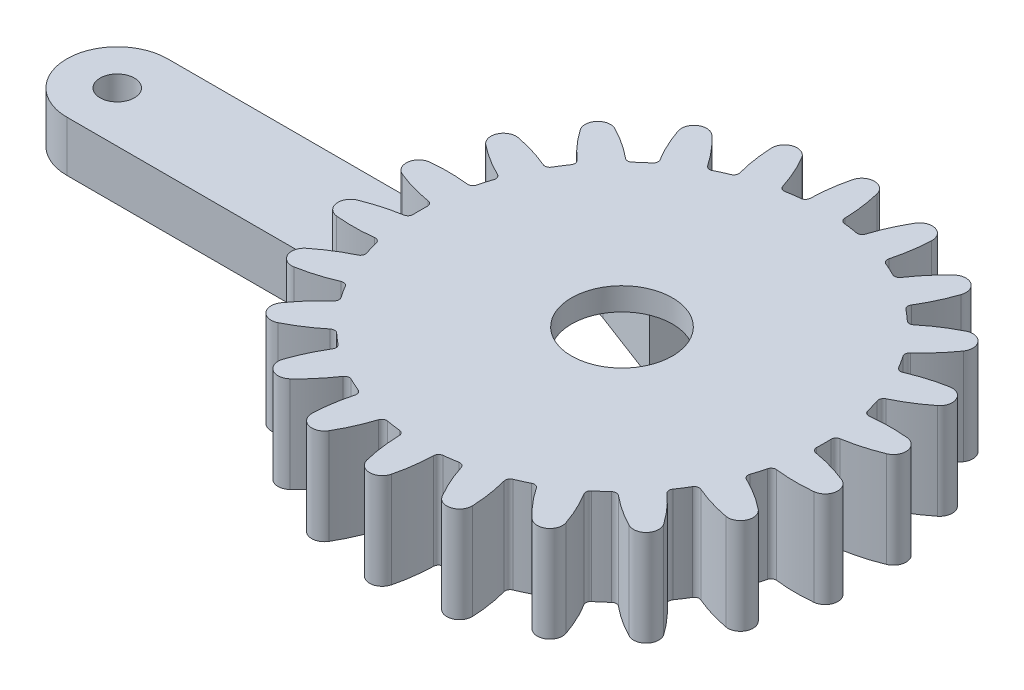
SolidWorks part; units mm, degrees
ref_plane "Front Plane" through (0, 0, 0) normal (0, 0, 1) x (1, 0, 0)
ref_plane "Top Plane" through (0, 0, 0) normal (0, 1, 0) x (1, 0, 0)
ref_plane "Right Plane" through (0, 0, 0) normal (1, 0, 0) x (0, 0, -1)
sketch "Sketch1" plane through (0, 0, 0) normal (0, 1, 0) x (1, 0, 0)
  line L20 (0, 25) -> (0, 20) construction
  line L21 (-15, 20) -> (15, 20) construction
  arc A6 (-2.1536, 19.8837) -> (-3.5355, 19.685) centre (0, 0) ccw
  circle A7 centre (0, 0) radius 25 construction
  arc A8 (1.2127, 24.0532) -> (-1.2127, 24.0532) centre (0, 23.75) ccw
  arc A9 (-1.2127, 24.0532) -> (-1.7076, 20.3697) centre (15, 20) ccw
  arc A10 (1.2127, 24.0532) -> (1.7076, 20.3697) centre (-15, 20) cw
  arc A11 (1.7076, 20.3697) -> (2.1536, 19.8837) centre (2.2074, 20.3808) ccw
  arc A12 (-1.7076, 20.3697) -> (-2.1536, 19.8837) centre (-2.2074, 20.3808) cw
  arc A13 (7.3772, 19.0636) -> (7.6682, 18.4715) centre (7.86, 18.9333) ccw
  arc A14 (7.9401, 22.7372) -> (7.3772, 19.0636) centre (-8.7577, 23.4158) cw
  arc A15 (5.613, 23.4205) -> (4.1004, 20.0257) centre (20.027, 14.9639) ccw
  arc A16 (4.1004, 20.0257) -> (3.5355, 19.685) centre (3.6239, 20.1771) cw
  arc A17 (7.9401, 22.7372) -> (5.613, 23.4205) centre (6.6911, 22.788) ccw
  arc A18 (12.4492, 16.2129) -> (12.5617, 15.5629) centre (12.8757, 15.952) ccw
  arc A19 (14.0243, 19.5792) -> (12.4492, 16.2129) centre (-1.806, 24.9347) cw
  arc A20 (11.984, 20.8904) -> (9.5762, 18.0593) centre (23.4316, 8.7155) ccw
  arc A21 (9.5762, 18.0593) -> (8.9382, 17.8916) centre (9.1617, 18.3389) cw
  arc A22 (14.0243, 19.5792) -> (11.984, 20.8904) centre (12.8402, 19.9798) ccw
  arc A23 (16.5126, 12.0489) -> (16.4374, 11.3935) centre (16.8483, 11.6783) ccw
  arc A24 (18.9723, 14.835) -> (16.5126, 12.0489) centre (5.2921, 24.4335) cw
  arc A25 (17.384, 16.668) -> (14.2762, 14.6298) centre (24.9379, 1.761) ccw
  arc A26 (14.2762, 14.6298) -> (13.6168, 14.6486) centre (13.9572, 15.0149) cw
  arc A27 (18.9723, 14.835) -> (17.384, 16.668) centre (17.9491, 15.5529) ccw
  arc A28 (19.2383, 6.9087) -> (18.9815, 6.301) centre (19.456, 6.4585) ccw
  arc A29 (22.3833, 8.889) -> (19.2383, 6.9087) centre (11.9614, 21.9528) cw
  arc A30 (21.3758, 11.0951) -> (17.8196, 10.0151) centre (24.4239, -5.3362) ccw
  arc A31 (17.8196, 10.0151) -> (17.1922, 10.219) centre (17.622, 10.4744) cw
  arc A32 (22.3833, 8.889) -> (21.3758, 11.0951) centre (21.6038, 9.8661) ccw
  arc A33 (20.4054, 1.2087) -> (19.9878, 0.6981) centre (20.4875, 0.7155) ccw
  arc A34 (23.9809, 2.2228) -> (20.4054, 1.2087) centre (17.6617, 17.6936) cw
  arc A35 (23.6358, 4.6235) -> (19.9194, 4.5891) centre (21.9312, -12.001) ccw
  arc A36 (19.9194, 4.5891) -> (19.3748, 4.9614) centre (19.8592, 5.0855) cw
  arc A37 (23.9809, 2.2228) -> (23.6358, 4.6235) centre (23.5083, 3.38) ccw
  arc A38 (19.9194, -4.5891) -> (19.3748, -4.9614) centre (19.8592, -5.0855) ccw
  arc A39 (23.6358, -4.6235) -> (19.9194, -4.5891) centre (21.9312, 12.001) cw
  arc A40 (23.9809, -2.2228) -> (20.4054, -1.2087) centre (17.6617, -17.6936) ccw
  arc A41 (20.4054, -1.2087) -> (19.9878, -0.6981) centre (20.4875, -0.7155) cw
  arc A42 (23.6358, -4.6235) -> (23.9809, -2.2228) centre (23.5083, -3.38) ccw
  arc A43 (17.8196, -10.0151) -> (17.1922, -10.219) centre (17.622, -10.4744) ccw
  arc A44 (21.3758, -11.0951) -> (17.8196, -10.0151) centre (24.4239, 5.3362) cw
  arc A45 (22.3833, -8.889) -> (19.2383, -6.9087) centre (11.9614, -21.9528) ccw
  arc A46 (19.2383, -6.9087) -> (18.9815, -6.301) centre (19.456, -6.4585) cw
  arc A47 (21.3758, -11.0951) -> (22.3833, -8.889) centre (21.6038, -9.8661) ccw
  arc A48 (14.2762, -14.6298) -> (13.6168, -14.6486) centre (13.9572, -15.0149) ccw
  arc A49 (17.384, -16.668) -> (14.2762, -14.6298) centre (24.9379, -1.761) cw
  arc A50 (18.9723, -14.835) -> (16.5126, -12.0489) centre (5.2921, -24.4335) ccw
  arc A51 (16.5126, -12.0489) -> (16.4374, -11.3935) centre (16.8483, -11.6783) cw
  arc A52 (17.384, -16.668) -> (18.9723, -14.835) centre (17.9491, -15.5529) ccw
  arc A53 (9.5762, -18.0593) -> (8.9382, -17.8916) centre (9.1617, -18.3389) ccw
  arc A54 (11.984, -20.8904) -> (9.5762, -18.0593) centre (23.4316, -8.7155) cw
  arc A55 (14.0243, -19.5792) -> (12.4492, -16.2129) centre (-1.806, -24.9347) ccw
  arc A56 (12.4492, -16.2129) -> (12.5617, -15.5629) centre (12.8757, -15.952) cw
  arc A57 (11.984, -20.8904) -> (14.0243, -19.5792) centre (12.8402, -19.9798) ccw
  arc A58 (4.1004, -20.0257) -> (3.5355, -19.685) centre (3.6239, -20.1771) ccw
  arc A59 (5.613, -23.4205) -> (4.1004, -20.0257) centre (20.027, -14.9639) cw
  arc A60 (7.9401, -22.7372) -> (7.3772, -19.0636) centre (-8.7577, -23.4158) ccw
  arc A61 (7.3772, -19.0636) -> (7.6682, -18.4715) centre (7.86, -18.9333) cw
  arc A62 (5.613, -23.4205) -> (7.9401, -22.7372) centre (6.6911, -22.788) ccw
  arc A63 (-1.7076, -20.3697) -> (-2.1536, -19.8837) centre (-2.2074, -20.3808) ccw
  arc A64 (-1.2127, -24.0532) -> (-1.7076, -20.3697) centre (15, -20) cw
  arc A65 (1.2127, -24.0532) -> (1.7076, -20.3697) centre (-15, -20) ccw
  arc A66 (1.7076, -20.3697) -> (2.1536, -19.8837) centre (2.2074, -20.3808) cw
  arc A67 (-1.2127, -24.0532) -> (1.2127, -24.0532) centre (0, -23.75) ccw
  arc A68 (-7.3772, -19.0636) -> (-7.6682, -18.4715) centre (-7.86, -18.9333) ccw
  arc A69 (-7.9401, -22.7372) -> (-7.3772, -19.0636) centre (8.7577, -23.4158) cw
  arc A70 (-5.613, -23.4205) -> (-4.1004, -20.0257) centre (-20.027, -14.9639) ccw
  arc A71 (-4.1004, -20.0257) -> (-3.5355, -19.685) centre (-3.6239, -20.1771) cw
  arc A72 (-7.9401, -22.7372) -> (-5.613, -23.4205) centre (-6.6911, -22.788) ccw
  arc A73 (-12.4492, -16.2129) -> (-12.5617, -15.5629) centre (-12.8757, -15.952) ccw
  arc A74 (-14.0243, -19.5792) -> (-12.4492, -16.2129) centre (1.806, -24.9347) cw
  arc A75 (-11.984, -20.8904) -> (-9.5762, -18.0593) centre (-23.4316, -8.7155) ccw
  arc A76 (-9.5762, -18.0593) -> (-8.9382, -17.8916) centre (-9.1617, -18.3389) cw
  arc A77 (-14.0243, -19.5792) -> (-11.984, -20.8904) centre (-12.8402, -19.9798) ccw
  arc A78 (-16.5126, -12.0489) -> (-16.4374, -11.3935) centre (-16.8483, -11.6783) ccw
  arc A79 (-18.9723, -14.835) -> (-16.5126, -12.0489) centre (-5.2921, -24.4335) cw
  arc A80 (-17.384, -16.668) -> (-14.2762, -14.6298) centre (-24.9379, -1.761) ccw
  arc A81 (-14.2762, -14.6298) -> (-13.6168, -14.6486) centre (-13.9572, -15.0149) cw
  arc A82 (-18.9723, -14.835) -> (-17.384, -16.668) centre (-17.9491, -15.5529) ccw
  arc A83 (-19.2383, -6.9087) -> (-18.9815, -6.301) centre (-19.456, -6.4585) ccw
  arc A84 (-22.3833, -8.889) -> (-19.2383, -6.9087) centre (-11.9614, -21.9528) cw
  arc A85 (-21.3758, -11.0951) -> (-17.8196, -10.0151) centre (-24.4239, 5.3362) ccw
  arc A86 (-17.8196, -10.0151) -> (-17.1922, -10.219) centre (-17.622, -10.4744) cw
  arc A87 (-22.3833, -8.889) -> (-21.3758, -11.0951) centre (-21.6038, -9.8661) ccw
  arc A88 (-20.4054, -1.2087) -> (-19.9878, -0.6981) centre (-20.4875, -0.7155) ccw
  arc A89 (-23.9809, -2.2228) -> (-20.4054, -1.2087) centre (-17.6617, -17.6936) cw
  arc A90 (-23.6358, -4.6235) -> (-19.9194, -4.5891) centre (-21.9312, 12.001) ccw
  arc A91 (-19.9194, -4.5891) -> (-19.3748, -4.9614) centre (-19.8592, -5.0855) cw
  arc A92 (-23.9809, -2.2228) -> (-23.6358, -4.6235) centre (-23.5083, -3.38) ccw
  arc A93 (-19.9194, 4.5891) -> (-19.3748, 4.9614) centre (-19.8592, 5.0855) ccw
  arc A94 (-23.6358, 4.6235) -> (-19.9194, 4.5891) centre (-21.9312, -12.001) cw
  arc A95 (-23.9809, 2.2228) -> (-20.4054, 1.2087) centre (-17.6617, 17.6936) ccw
  arc A96 (-20.4054, 1.2087) -> (-19.9878, 0.6981) centre (-20.4875, 0.7155) cw
  arc A97 (-23.6358, 4.6235) -> (-23.9809, 2.2228) centre (-23.5083, 3.38) ccw
  arc A98 (-17.8196, 10.0151) -> (-17.1922, 10.219) centre (-17.622, 10.4744) ccw
  arc A99 (-21.3758, 11.0951) -> (-17.8196, 10.0151) centre (-24.4239, -5.3362) cw
  arc A100 (-22.3833, 8.889) -> (-19.2383, 6.9087) centre (-11.9614, 21.9528) ccw
  arc A101 (-19.2383, 6.9087) -> (-18.9815, 6.301) centre (-19.456, 6.4585) cw
  arc A102 (-21.3758, 11.0951) -> (-22.3833, 8.889) centre (-21.6038, 9.8661) ccw
  arc A103 (-14.2762, 14.6298) -> (-13.6168, 14.6486) centre (-13.9572, 15.0149) ccw
  arc A104 (-17.384, 16.668) -> (-14.2762, 14.6298) centre (-24.9379, 1.761) cw
  arc A105 (-18.9723, 14.835) -> (-16.5126, 12.0489) centre (-5.2921, 24.4335) ccw
  arc A106 (-16.5126, 12.0489) -> (-16.4374, 11.3935) centre (-16.8483, 11.6783) cw
  arc A107 (-17.384, 16.668) -> (-18.9723, 14.835) centre (-17.9491, 15.5529) ccw
  arc A108 (-9.5762, 18.0593) -> (-8.9382, 17.8916) centre (-9.1617, 18.3389) ccw
  arc A109 (-11.984, 20.8904) -> (-9.5762, 18.0593) centre (-23.4316, 8.7155) cw
  arc A110 (-14.0243, 19.5792) -> (-12.4492, 16.2129) centre (1.806, 24.9347) ccw
  arc A111 (-12.4492, 16.2129) -> (-12.5617, 15.5629) centre (-12.8757, 15.952) cw
  arc A112 (-11.984, 20.8904) -> (-14.0243, 19.5792) centre (-12.8402, 19.9798) ccw
  arc A113 (-4.1004, 20.0257) -> (-3.5355, 19.685) centre (-3.6239, 20.1771) ccw
  arc A114 (-5.613, 23.4205) -> (-4.1004, 20.0257) centre (-20.027, 14.9639) cw
  arc A115 (-7.9401, 22.7372) -> (-7.3772, 19.0636) centre (8.7577, 23.4158) ccw
  arc A116 (-7.3772, 19.0636) -> (-7.6682, 18.4715) centre (-7.86, 18.9333) cw
  arc A117 (-5.613, 23.4205) -> (-7.9401, 22.7372) centre (-6.6911, 22.788) ccw
  arc A118 (-19.9878, 0.6981) -> (-19.9878, -0.6981) centre (0, 0) ccw
  arc A119 (-18.9815, 6.301) -> (-19.3748, 4.9614) centre (0, 0) ccw
  arc A120 (-19.3748, -4.9614) -> (-18.9815, -6.301) centre (0, 0) ccw
  arc A121 (-17.1922, -10.219) -> (-16.4374, -11.3935) centre (0, 0) ccw
  arc A122 (-13.6168, -14.6486) -> (-12.5617, -15.5629) centre (0, 0) ccw
  arc A123 (-8.9382, -17.8916) -> (-7.6682, -18.4715) centre (0, 0) ccw
  arc A124 (-3.5355, -19.685) -> (-2.1536, -19.8837) centre (0, 0) ccw
  arc A125 (2.1536, -19.8837) -> (3.5355, -19.685) centre (0, 0) ccw
  arc A126 (7.6682, -18.4715) -> (8.9382, -17.8916) centre (0, 0) ccw
  arc A127 (12.5617, -15.5629) -> (13.6168, -14.6486) centre (0, 0) ccw
  arc A128 (18.9815, -6.301) -> (19.3748, -4.9614) centre (0, 0) ccw
  arc A129 (16.4374, -11.3935) -> (17.1922, -10.219) centre (0, 0) ccw
  arc A130 (19.9878, -0.6981) -> (19.9878, 0.6981) centre (0, 0) ccw
  arc A131 (19.3748, 4.9614) -> (18.9815, 6.301) centre (0, 0) ccw
  arc A132 (17.1922, 10.219) -> (16.4374, 11.3935) centre (0, 0) ccw
  arc A133 (13.6168, 14.6486) -> (12.5617, 15.5629) centre (0, 0) ccw
  arc A134 (-16.4374, 11.3935) -> (-17.1922, 10.219) centre (0, 0) ccw
  arc A135 (-12.5617, 15.5629) -> (-13.6168, 14.6486) centre (0, 0) ccw
  arc A136 (-7.6682, 18.4715) -> (-8.9382, 17.8916) centre (0, 0) ccw
  arc A137 (3.5355, 19.685) -> (2.1536, 19.8837) centre (0, 0) ccw
  arc A138 (8.9382, 17.8916) -> (7.6682, 18.4715) centre (0, 0) ccw
  point P36 (0, 0)
  point P42 (0, 20)
  point P60 (1.7115, 19.9266)
  point P63 (-1.7115, 19.9266)
  point P284 (0, 0)
  dimension "D6" = 40
  dimension "D7" = 50
  dimension "D9" = 2.5
  dimension "D11" = 0.5
  dimension "D8" = 5
  dimension "D10" = 20
  dimension "D12" = 22
extrude "Boss-Extrude1" add sketch "Sketch1" along normal blind 10
sketch "Sketch2" plane through (0, 0, 0) normal (0, -1, 0) x (1, 0, 0)
  line L0 (0, 0) -> (-50, 0) construction
  line L1 (0, -5) -> (-50, -5)
  line L2 (0, 5) -> (-50, 5)
  arc A0 (0, -5) -> (0, 5) centre (0, 0) ccw
  arc A1 (-50, 5) -> (-50, -5) centre (-50, 0) ccw
  circle A2 centre (-50, 0) radius 1.7
  point P3 (-25, 0)
  dimension "D2" = 10
  dimension "D3" = 3.4
  dimension "D1" = 50
extrude "Boss-Extrude2" add sketch "Sketch2" against normal blind 5
sketch "Sketch3" plane through (0, 10, 0) normal (0, 1, 0) x (1, 0, 0)
  circle A0 centre (0, 0) radius 5
  dimension "D1" = 10
extrude "Cut-Extrude1" cut sketch "Sketch3" against normal blind 10
sketch "Sketch4" plane through (0, 0, 0) normal (0, -1, 0) x (1, 0, 0)
  line L0 (0, 0) -> (0, 14) construction
  line L1 (-3.75, 6.5) -> (3.75, 6.5) construction
  line L2 (-3.75, 6.5) -> (-2.4677, 14.4005)
  line L3 (3.75, 6.5) -> (2.4677, 14.4005)
  line L4 (3.7542, 6.4976) -> (11.2374, 9.3374)
  line L5 (7.5042, 0.0024) -> (13.7051, 5.0632)
  line L6 (7.5042, -0.0024) -> (13.7051, -5.0632)
  line L7 (3.7542, -6.4976) -> (11.2374, -9.3374)
  line L8 (3.75, -6.5) -> (2.4677, -14.4005)
  line L9 (-3.75, -6.5) -> (-2.4677, -14.4005)
  line L10 (-3.7542, -6.4976) -> (-11.2374, -9.3374)
  line L11 (-7.5042, -0.0024) -> (-13.7051, -5.0632)
  line L12 (-7.5042, 0.0024) -> (-13.7051, 5.0632)
  line L13 (-3.7542, 6.4976) -> (-11.2374, 9.3374)
  line L14 (-3.7542, 6.4976) -> (-3.75, 6.5)
  line L15 (3.75, 6.5) -> (3.7542, 6.4976)
  line L16 (7.5042, -0.0024) -> (7.5042, 0.0024)
  line L17 (-7.5042, 0.0024) -> (-7.5042, -0.0024)
  line L18 (-3.75, -6.5) -> (-3.7542, -6.4976)
  line L19 (3.7542, -6.4976) -> (3.75, -6.5)
  arc A0 (2.4677, 14.4005) -> (-2.4677, 14.4005) centre (0, 14) ccw
  arc A1 (13.7051, 5.0632) -> (11.2374, 9.3374) centre (12.1244, 7) ccw
  arc A2 (11.2374, -9.3374) -> (13.7051, -5.0632) centre (12.1244, -7) ccw
  arc A3 (-2.4677, -14.4005) -> (2.4677, -14.4005) centre (0, -14) ccw
  arc A4 (-13.7051, -5.0632) -> (-11.2374, -9.3374) centre (-12.1244, -7) ccw
  arc A5 (-11.2374, 9.3374) -> (-13.7051, 5.0632) centre (-12.1244, 7) ccw
  point P5 (0, 6.5)
  point P35 (0, 0)
  dimension "D3" = 5
  dimension "D1" = 14
  dimension "D2" = 6.5
  dimension "D4" = 7.5
  dimension "D5" = 6
extrude "Cut-Extrude2" cut sketch "Sketch4" against normal blind 7.25
sketch "Sketch5" plane through (0, 10, 0) normal (0, 1, 0) x (1, 0, 0)
  line L1 (25.9994, -26.3179) -> (-25.9994, -26.3179)
  line L2 (25.9994, -26.3179) -> (25.9994, 26.3179)
  line L3 (25.9994, 26.3179) -> (-25.9994, 26.3179)
  line L4 (-25.9994, -26.3179) -> (-25.9994, 26.3179)
  line L5 (25.9994, -26.3179) -> (-25.9994, 26.3179) construction
  line L6 (25.9994, 26.3179) -> (-25.9994, -26.3179) construction
  point P0 (0, 0)
extrude "Cut-Extrude3" cut sketch "Sketch5" against normal blind 0.5
